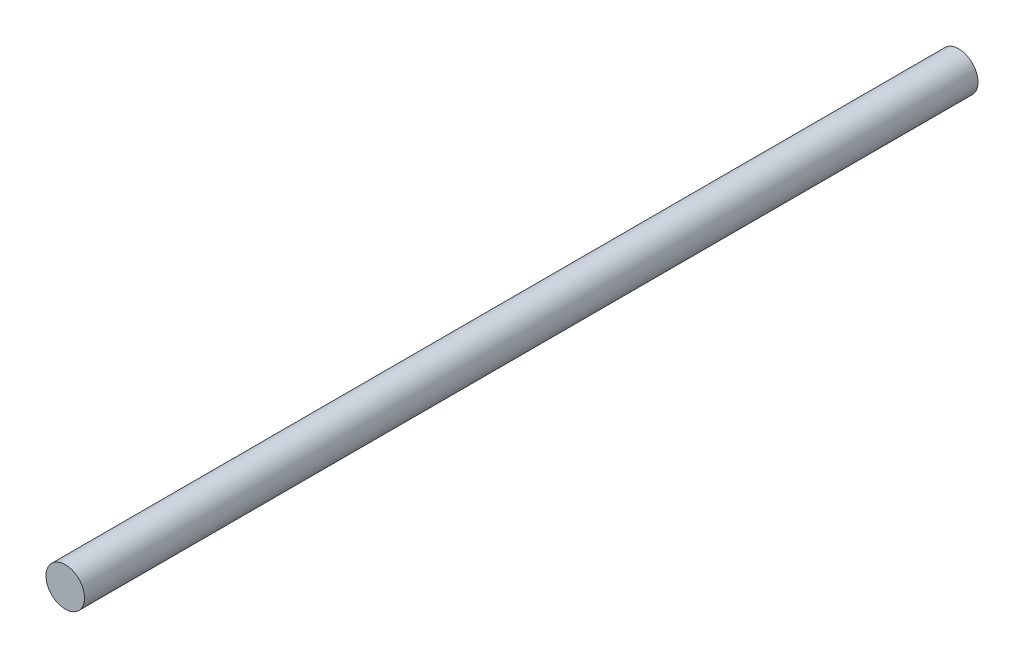
SolidWorks part; units mm, degrees
ref_plane "前视基准面" through (0, 0, 0) normal (0, 0, 1) x (1, 0, 0)
ref_plane "上视基准面" through (0, 0, 0) normal (0, 1, 0) x (1, 0, 0)
ref_plane "右视基准面" through (0, 0, 0) normal (1, 0, 0) x (0, 0, -1)
other "Configuration Table"
sketch "草图1" plane through (0, 0, 0) normal (0, 0, 1) x (1, 0, 0)
  circle A0 centre (0, 0) radius 3
  dimension "D1" = 6
extrude "凸台-拉伸1" add sketch "草图1" along normal blind 139
